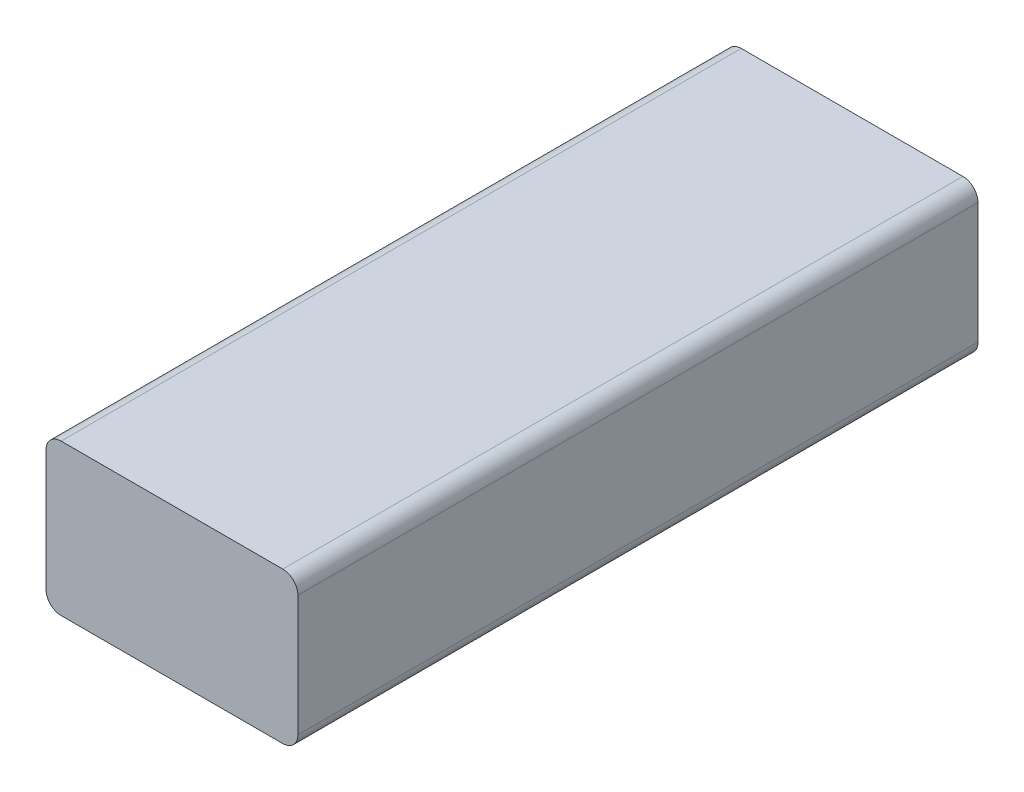
SolidWorks part; units mm, degrees
ref_plane "前视基准面" through (0, 0, 0) normal (0, 0, 1) x (1, 0, 0)
ref_plane "上视基准面" through (0, 0, 0) normal (0, 1, 0) x (1, 0, 0)
ref_plane "右视基准面" through (0, 0, 0) normal (1, 0, 0) x (0, 0, -1)
sketch "草图1" plane through (0, 0, 0) normal (1, 0, 0) x (0, 0, -1)
  line L1 (-67.5, 15) -> (67.5, 15)
  line L2 (-67.5, 15) -> (-67.5, -15)
  line L3 (-67.5, -15) -> (67.5, -15)
  line L4 (67.5, 15) -> (67.5, -15)
  line L5 (-67.5, 15) -> (67.5, -15) construction
  line L6 (-67.5, -15) -> (67.5, 15) construction
  point P0 (0, 0)
extrude "凸台-拉伸1" add sketch "草图1" along normal blind 50
fillet "圆角1" radius 3 4 edges at (0, -15, 0) (0, 15, 0) (50, 15, 0) (50, -15, 0)
